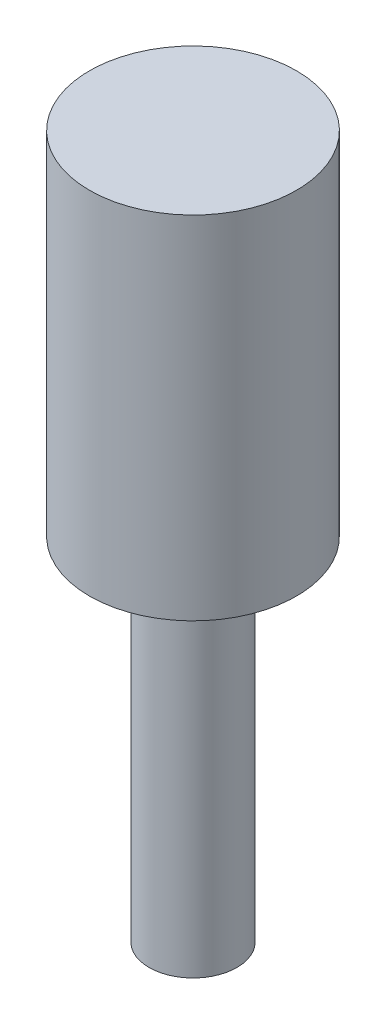
SolidWorks part; units mm, degrees
ref_plane "Front Plane" through (0, 0, 0) normal (0, 0, 1) x (1, 0, 0)
ref_plane "Top Plane" through (0, 0, 0) normal (0, 1, 0) x (1, 0, 0)
ref_plane "Right Plane" through (0, 0, 0) normal (1, 0, 0) x (0, 0, -1)
sketch "Sketch1" plane through (0, 0, 0) normal (0, 1, 0) x (1, 0, 0)
  circle A0 centre (0, 0) radius 3.175
  dimension "D1" = 6.35
extrude "Boss-Extrude1" add sketch "Sketch1" along normal blind 25.4
sketch "Sketch2" plane through (0, 25.4, 0) normal (0, 1, 0) x (1, 0, 0)
  circle A0 centre (0, 0) radius 7.4836
extrude "Boss-Extrude2" add sketch "Sketch2" along normal blind 25.4
